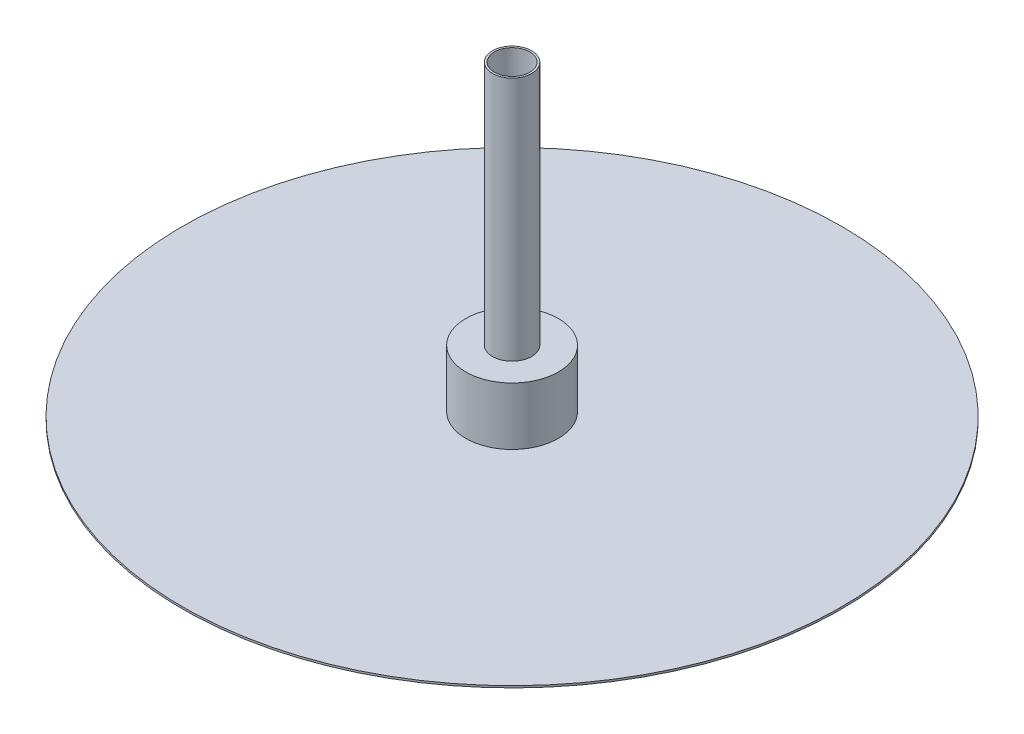
SolidWorks part; units mm, degrees
ref_plane "Front Plane" through (0, 0, 0) normal (0, 0, 1) x (1, 0, 0)
ref_plane "Top Plane" through (0, 0, 0) normal (0, 1, 0) x (1, 0, 0)
ref_plane "Right Plane" through (0, 0, 0) normal (1, 0, 0) x (0, 0, -1)
sketch "Sketch3" plane through (0, 0, 0) normal (0, 0, 1) x (1, 0, 0)
  line L0 (0, 0) -> (0, 131.85) construction
sketch "Sketch5" plane through (0, 0, 0) normal (0, 0, 1) x (1, 0, 0)
  line L0 (0, 0) -> (-258.2053, 0) construction
sketch "Sketch2" plane through (0, 0, 0) normal (0, 0, 1) x (1, 0, 0)
  line L0 (25.4925, 0) -> (-25.4925, 0) construction
  line L1 (-31.75, 500) -> (-28.575, 500)
  line L2 (-31.75, 500) -> (-31.75, 0)
  line L3 (-31.75, 0) -> (-28.575, 0)
  line L4 (-28.575, 500) -> (-28.575, 0)
  line L5 (-31.75, 100) -> (-71.75, 100)
  line L6 (-71.75, 100) -> (-71.75, 10)
  line L7 (-71.75, 10) -> (-74.925, 10)
  line L8 (-74.925, 10) -> (-74.925, 103.175)
  line L9 (-74.925, 103.175) -> (-31.75, 103.175)
  line L10 (200000, 0) -> (-200258.2053, 0) construction
  line L12 (-31.75, 0) -> (-28.575, 0)
  line L13 (-31.75, 0) -> (-31.75, -100)
  line L14 (-31.75, -100) -> (-28.575, -100)
  line L15 (-28.575, 0) -> (-28.575, -100)
  dimension "D1" = 31.75
  dimension "D2" = 3.175
  dimension "D3" = 500
  dimension "D4" = 3.175
  dimension "D5" = 3.175
  dimension "D6" = 40
  dimension "D7" = 100
  dimension "D8" = 10
  dimension "D9" = 100
revolve "Revolve1" add sketch "Sketch2" angle 360 about L0
sketch "Sketch6" plane through (0, 0, 0) normal (0, 0, 1) x (1, 0, 0)
  line L0 (200000, 0) -> (-200258.2053, 0) construction
  line L1 (-533.3375, 0) -> (-33.3375, 0)
  line L2 (-533.3375, 0) -> (-533.3375, 3.175)
  line L3 (-533.3375, 3.175) -> (-33.3375, 3.175)
  line L4 (-33.3375, 0) -> (-33.3375, 3.175)
  line L5 (-31.75, 500) -> (-31.75, 0) construction
  line L6 (-31.75, 100) -> (-71.75, 100) construction
  line L7 (-33.3375, 3.175) -> (-36.5125, 3.175)
  line L8 (-33.3375, 3.175) -> (-33.3375, 96.825)
  line L9 (-33.3375, 96.825) -> (-36.5125, 96.825)
  line L10 (-36.5125, 3.175) -> (-36.5125, 96.825)
  line L11 (-71.75, 10) -> (71.75, 10) construction
  line L12 (-36.5125, 10) -> (-61.1306, 10)
  line L13 (-36.5125, 10) -> (-36.5125, 13.175)
  line L14 (-36.5125, 13.175) -> (-61.1306, 13.175)
  line L15 (-61.1306, 10) -> (-61.1306, 13.175)
  line L17 (-61.1306, 13.175) -> (-57.9556, 13.175)
  line L18 (-61.1306, 13.175) -> (-61.1306, 80)
  line L19 (-61.1306, 80) -> (-57.9556, 80)
  line L20 (-57.9556, 13.175) -> (-57.9556, 80)
  dimension "D1" = 500
  dimension "D2" = 3.175
  dimension "D3" = 1.5875
  dimension "D4" = 3.175
  dimension "D5" = 3.175
  dimension "D6" = 3.175
  dimension "D7" = 20
  dimension "D8" = 21.4431
  dimension "D9" = 3.175
revolve "Revolve2" add sketch "Sketch6" angle 360 about L0
sketch "Sketch8" plane through (0, 13.175, 0) normal (0, 1, 0) x (1, 0, 0)
  line L0 (0, 0) -> (-45, 0)
  line L1 (200000, 0) -> (-200258.2053, 0) construction
  circle A0 centre (-45, 0) radius 2.5
  dimension "D1" = 5
  dimension "D2" = 45
extrude "Cut-Extrude1" cut sketch "Sketch8" along direction (0, -1, 0) on the side against the normal up to surface (3.175 mm away)
